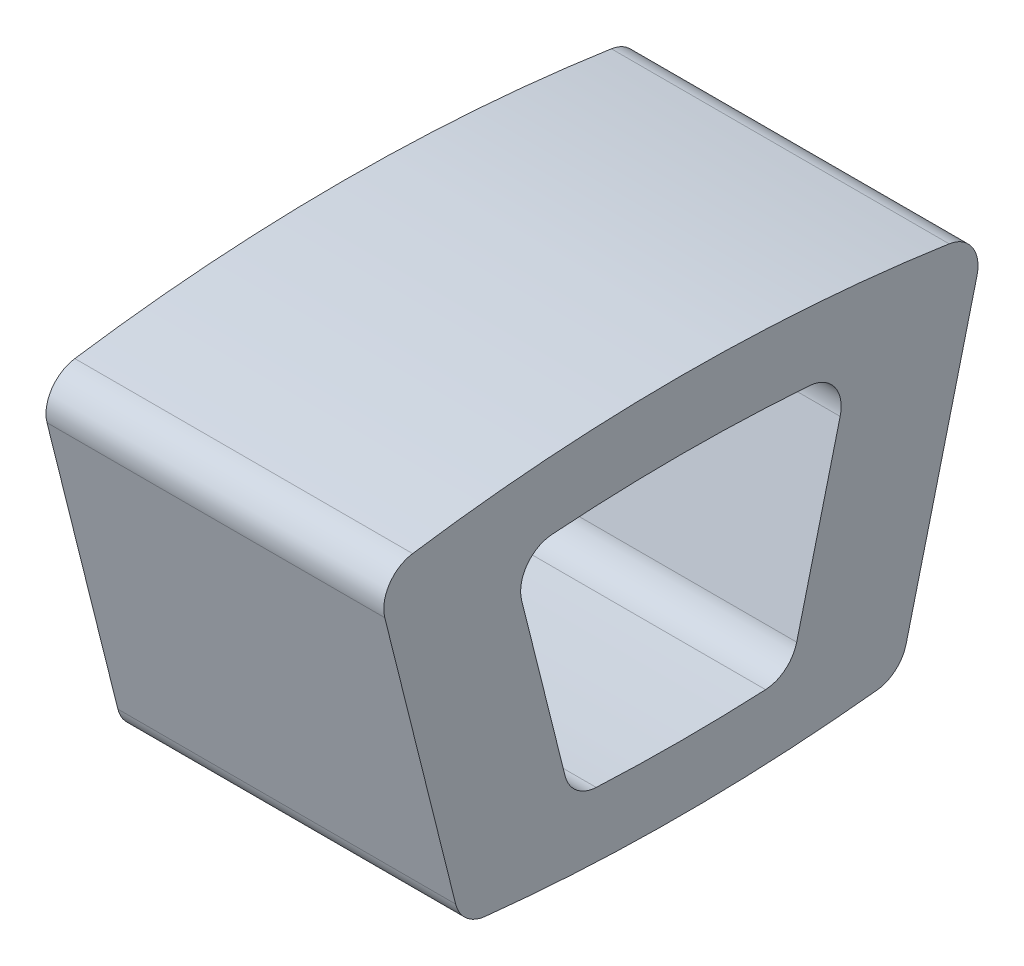
SolidWorks part; units mm, degrees
ref_plane "Спереди" through (0, 0, 0) normal (0, 0, 1) x (1, 0, 0)
ref_plane "Сверху" through (0, 0, 0) normal (0, 1, 0) x (1, 0, 0)
ref_plane "Справа" through (0, 0, 0) normal (1, 0, 0) x (0, 0, -1)
sketch "Эскиз1" plane through (0, 0, 0) normal (1, 0, 0) x (0, 0, -1)
  line L0 (13.7153, 182.8612) -> (18.8603, 203.441)
  line L1 (-13.7153, 182.8612) -> (-18.8603, 203.441)
  line L2 (0, 0) -> (0, 218) construction
  line L3 (26.6724, 176.1896) -> (35.0647, 209.7586)
  line L4 (-26.6724, 176.1896) -> (-35.0647, 209.7586)
  arc A0 (-10.0267, 179.8359) -> (10.0267, 179.8359) centre (0, 388.5545) ccw
  arc A1 (-15.272, 208.4005) -> (15.272, 208.4005) centre (0, 0) cw
  arc A2 (-23.2198, 173.1827) -> (23.2198, 173.1827) centre (0, 388.9606) ccw
  arc A3 (-31.7696, 214.6857) -> (31.7696, 214.6857) centre (0, 0) cw
  arc A4 (10.0267, 179.8359) -> (13.7153, 182.8612) centre (9.8347, 183.8313) ccw
  arc A5 (15.272, 208.4005) -> (18.8603, 203.441) centre (14.9797, 204.4112) cw
  arc A6 (-13.7153, 182.8612) -> (-10.0267, 179.8359) centre (-9.8347, 183.8313) ccw
  arc A7 (-18.8603, 203.441) -> (-15.272, 208.4005) centre (-14.9797, 204.4112) cw
  arc A8 (23.2198, 173.1827) -> (26.6724, 176.1896) centre (22.7918, 177.1597) ccw
  arc A9 (31.7696, 214.6857) -> (35.0647, 209.7586) centre (31.1841, 210.7288) cw
  arc A10 (-26.6724, 176.1896) -> (-23.2198, 173.1827) centre (-22.7918, 177.1597) ccw
  arc A11 (-35.0647, 209.7586) -> (-31.7696, 214.6857) centre (-31.1841, 210.7288) cw
  dimension "D2" = 4
  dimension "D1" = 4
  dimension "D3" = 4
  dimension "D4" = 4
  dimension "D6" = 4
  dimension "D5" = 4
  dimension "D8" = 4
  dimension "D9" = 4
  dimension "D7" = 14.1883
extrude "Вытянуть1" add sketch "Эскиз1" along normal blind 40
